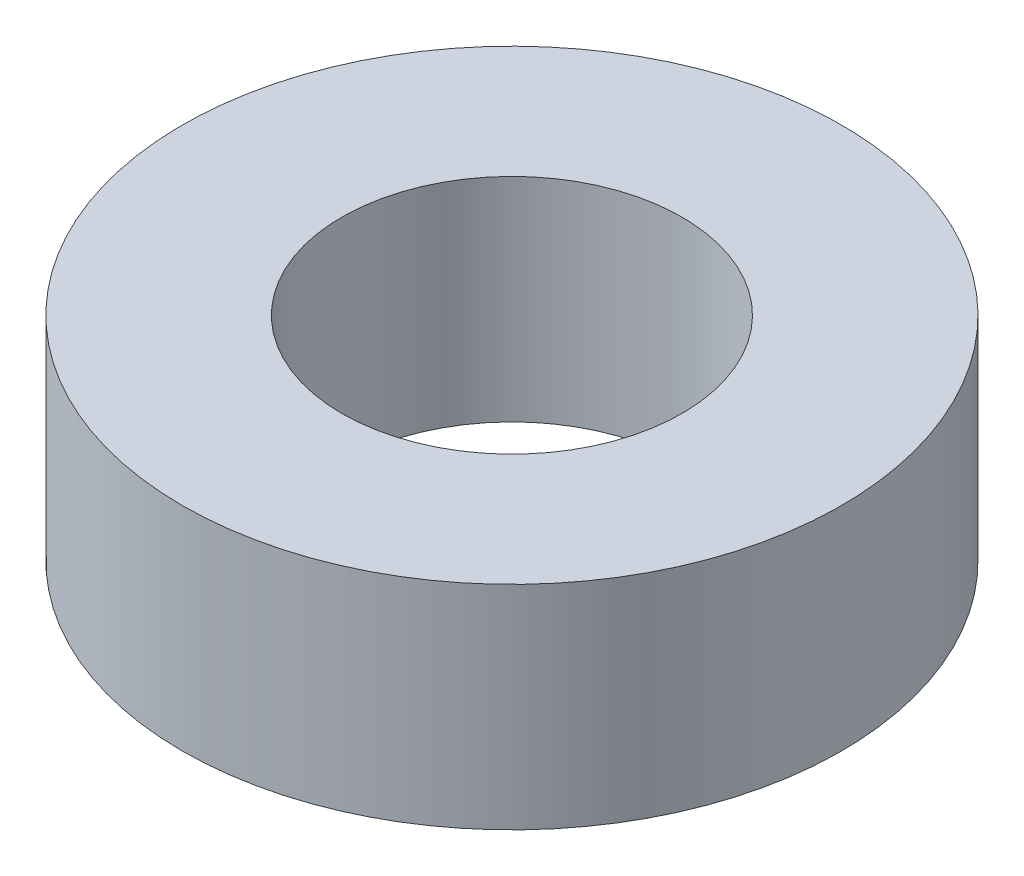
SolidWorks part; units mm, degrees
ref_plane "Front Plane" through (0, 0, 0) normal (0, 0, 1) x (1, 0, 0)
ref_plane "Top Plane" through (0, 0, 0) normal (0, 1, 0) x (1, 0, 0)
ref_plane "Right Plane" through (0, 0, 0) normal (1, 0, 0) x (0, 0, -1)
sketch "Sketch1" plane through (0, 0, 0) normal (0, 1, 0) x (1, 0, 0)
  circle A0 centre (0, 0) radius 1.6
  circle A1 centre (0, 0) radius 3.1
  dimension "D1" = 3.2
  dimension "D2" = 6.2
extrude "Boss-Extrude1" add sketch "Sketch1" along normal blind 2
